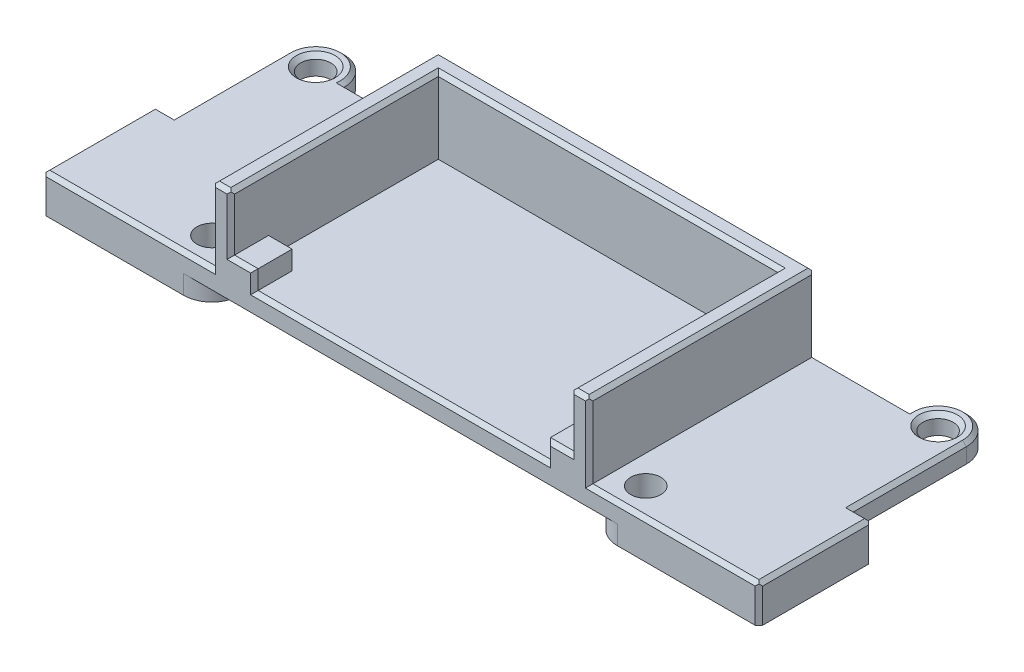
SolidWorks part; units mm, degrees
material "镁合金"
ref_plane "前视基准面" through (0, 0, 0) normal (0, 0, 1) x (1, 0, 0)
ref_plane "上视基准面" through (0, 0, 0) normal (0, 1, 0) x (1, 0, 0)
ref_plane "右视基准面" through (0, 0, 0) normal (1, 0, 0) x (0, 0, -1)
sketch "草图1" plane through (0, 0, 0) normal (0, 1, 0) x (1, 0, 0)
  line L1 (-18, 4) -> (18, 4)
  line L2 (-18, 4) -> (-18, -4)
  line L3 (-18, -4) -> (18, -4)
  line L4 (18, 4) -> (18, -4)
  line L5 (-18, 4) -> (18, -4) construction
  line L6 (-18, -4) -> (18, 4) construction
  line L7 (-18, -4) -> (-15, -4)
  line L8 (-18, -4) -> (-18, -1)
  line L9 (-18, -1) -> (-15, -1)
  line L10 (-15, -4) -> (-15, -1)
  line L11 (18, -4) -> (15, -4)
  line L12 (18, -4) -> (18, -1)
  line L13 (18, -1) -> (15, -1)
  line L14 (15, -4) -> (15, -1)
  line L15 (-19, -2) -> (19, -2)
  line L16 (-19, -2) -> (-19, -8)
  line L17 (-19, -8) -> (19, -8)
  line L18 (19, -2) -> (19, -8)
  circle A0 centre (16.5, 4) radius 1.5
  circle A1 centre (-16.5, 4) radius 1.5
  point P0 (0, 0)
  dimension "D3" = 3
  dimension "D4" = 3
  dimension "D1" = 36
  dimension "D2" = 8
  dimension "D5" = 3
  dimension "D6" = 3
  dimension "D7" = 3
  dimension "D8" = 3
  dimension "D9" = 38
  dimension "D10" = 6
  dimension "D11" = 1
  dimension "D12" = 2
extrude "凸台-拉伸1" add sketch "草图1" along normal blind 1 contours A1 L2 L9 L10 L3 L14 L13 L4 A0 L1 | L1 A1 | L1 A1 | L1 A0 | L1 A0 | L14 L3 L4 L13 | L3 L10 L9 L2 | L15 L10 L3 L14 | L15 L8 L3 L10 | L18 L15 L12 L3 L8 L16 L17 | L15 L14 L3 L12
sketch "草图2" plane through (0, 1, 0) normal (0, 1, 0) x (1, 0, 0)
  line L0 (-9, 3) -> (-9, -7)
  line L1 (-15, 4) -> (15, 4) construction
  line L2 (-10, 4) -> (10, 4)
  line L3 (-10, 4) -> (-10, -8)
  line L4 (-10, -8) -> (10, -8)
  line L5 (10, 4) -> (10, -8)
  line L6 (-19, -8) -> (19, -8) construction
  line L7 (-9, -7) -> (9, -7)
  line L8 (9, 3) -> (9, -7)
  line L9 (-9, 3) -> (9, 3)
  point P9 (0, -8)
  dimension "D1" = 20
  dimension "D2" = 1
extrude "凸台-拉伸4" add sketch "草图2" along normal blind 4
sketch "草图8" plane through (0, 0, 8) normal (0, 0, 1) x (1, 0, 0)
  line L0 (-10, 5) -> (10, 5) construction
  line L1 (-9, 5) -> (9, 5)
  line L2 (-9, 5) -> (-9, 1)
  line L3 (-9, 1) -> (9, 1)
  line L4 (9, 5) -> (9, 1)
  line L5 (-10, 5) -> (-10, 1) construction
  line L6 (10, 5) -> (10, 1) construction
  line L7 (-19, 0) -> (19, 0) construction
  dimension "D1" = 1
  dimension "D2" = 1
  dimension "D3" = 1
extrude "切除-拉伸2" cut sketch "草图8" against normal blind 4
sketch "草图9" plane through (0, 0, 8) normal (0, 0, 1) x (1, 0, 0)
  line L1 (-9, 1) -> (-7.75, 1)
  line L2 (-9, 1) -> (-9, 2)
  line L3 (-9, 2) -> (-7.75, 2)
  line L4 (-7.75, 1) -> (-7.75, 2)
  line L5 (9, 1) -> (7.75, 1)
  line L6 (9, 1) -> (9, 2)
  line L7 (9, 2) -> (7.75, 2)
  line L8 (7.75, 1) -> (7.75, 2)
  dimension "D1" = 1.25
  dimension "D2" = 1
  dimension "D3" = 1
  dimension "D4" = 1.25
extrude "凸台-拉伸5" add sketch "草图9" against normal blind 2
sketch "草图10" plane through (0, 0, 0) normal (0, -1, 0) x (1, 0, 0)
  line L1 (-19, 8) -> (-13, 8)
  line L2 (-19, 8) -> (-19, 2)
  line L3 (-19, 2) -> (-13, 2)
  line L4 (-13, 8) -> (-13, 2)
  line L5 (19, 8) -> (13, 8)
  line L6 (19, 8) -> (19, 2)
  line L7 (19, 2) -> (13, 2)
  line L8 (13, 8) -> (13, 2)
  line L9 (-13, 8) -> (-11.5, 8)
  line L10 (-13, 8) -> (-13, 5)
  line L11 (-13, 5) -> (-11.5, 5)
  line L12 (-11.5, 8) -> (-11.5, 5)
  line L13 (13, 8) -> (11.5, 8)
  line L14 (13, 8) -> (13, 5)
  line L15 (13, 5) -> (11.5, 5)
  line L16 (11.5, 8) -> (11.5, 5)
  circle A0 centre (-11.5, 6.5) radius 1.5
  circle A1 centre (11.5, 6.5) radius 1.5
  line M11 (18, 2) -> (19, 2)
  line M12 (19, 2) -> (19, 8)
  line M13 (19, 8) -> (-19, 8)
  line M14 (-19, 8) -> (-19, 2)
  line M15 (-19, 2) -> (-18, 2)
  dimension "D5" = 3
  dimension "D6" = 1.5
  dimension "D8" = 3
  dimension "D1" = 6
  dimension "D2" = 6
  dimension "D3" = 6
  dimension "D4" = 6
  dimension "D7" = 1.5
extrude "凸台-拉伸6" add sketch "草图10" along normal blind 1 contours L4 L3 L10 M13 M14 M15 | A0 L10 L11 | L12 A0 | L12 A0 | A0 L4 M13 | L16 A1 | L16 A1 | A1 L8 M13 | A1 L15 L14 | L8 L14 L7 M13 M11 M12
hole_wizard "M2 螺纹孔1" positions "草图11" profile "草图12" tap size "M2" standard "GB"
sketch "草图11" plane through (0, 1, 0) normal (0, 1, 0) x (1, 0, 0)
  point P0 (-16.5, 4)
  point P3 (16.5, 4)
sketch "草图12" plane through (-16.5, 1, -4) normal (1, 0, 0) x (0, 0, 1)
  line L0 (0, 0) -> (0, 5.9807)
  line L1 (0, 5.9807) -> (0.8, 5.5)
  line L2 (0.8, 5.5) -> (0.8, 0.225)
  line L3 (0.8, 0.225) -> (1.025, 0)
  line L5 (1.025, 0) -> (0, 0)
  line L6 (-0.8, 0.225) -> (-1.025, 0) construction
  line L10 (0, 5.9807) -> (-0.8, 5.5) construction
  line L11 (0, -6.35) -> (0, 107.95) construction
  dimension "螺纹孔钻头直径" = 1.6
  dimension "螺纹孔钻头深度" = 5.5
  dimension "近端锥形沉头孔直径" = 2.05
  dimension "近端锥形沉头孔角度" = 90
  dimension "导头角度" = 118
cosmetic thread "孔螺蚊线1" parameters "D1"=1, "D2"=2
cosmetic thread "孔螺蚊线2" parameters "D1"=1, "D2"=2
hole_wizard "M2 螺纹孔2" positions "草图13" profile "草图14" tap size "M2" standard "GB" end condition up to next
sketch "草图13" plane through (0, -1, 0) normal (0, -1, 0) x (-1, 0, 0)
  point P0 (11.5, -6.5)
  point P3 (-11.5, -6.5)
cosmetic thread "孔螺蚊线3" parameters "D2"=2
cosmetic thread "孔螺蚊线4" parameters "D2"=2
sketch "草图14" plane through (-11.5, -1, 6.5) normal (1, 0, 0) x (0, 0, -1)
  line L0 (0, 0) -> (0, 2)
  line L1 (0, 2) -> (0.8, 2)
  line L2 (0.8, 2) -> (0.8, 0.225)
  line L3 (0.8, 0.225) -> (1.025, 0)
  line L5 (1.025, 0) -> (0, 0)
  line L6 (-0.8, 0.225) -> (-1.025, 0) construction
  line L11 (0, -6.35) -> (0, 107.95) construction
  dimension "通孔螺纹孔钻头直径" = 1.6
  dimension "通孔螺纹孔钻头深度" = 2
  dimension "近端锥形沉头孔直径" = 2.05
  dimension "近端锥形沉头孔角度" = 90
chamfer "倒角1" distance 0.2 angle 45 8 edges at (9.5, 5, 8) (9, 5, 2.5) (0, 5, -3) (-9, 5, 2.5) (-9.5, 5, 8) (-10, 5, 2) (0, 5, -4) (10, 5, 2)
chamfer "倒角2" distance 0.2 angle 45 12 edges at (-14.5, 1, 8) (-19, 1, 5) (-18.5, 1, 2) (-18, 1, -1) (-16.5, 1, -5.5) (-12.5, 1, -4) (12.5, 1, -4) (16.5, 1, -5.5) (18, 1, -1) (18.5, 1, 2) (19, 1, 5) (14.5, 1, 8)
chamfer "倒角3" distance 0.2 angle 45 11 edges at (7.75, 1.5, 8) (-9, 3.4, 8) (-10, 2.8, 8) (10, 2.8, 8) (-10, 0.9, 7.9) (10, 0.9, 7.9) (0, 1, 8) (-7.75, 1.5, 8) (-8.375, 2, 8) (9, 3.4, 8) (8.375, 2, 8)
chamfer "倒角4" distance 0.2 angle 45 4 edges at (19, -0.1, 2) (19, -0.1, 8) (-19, -0.1, 8) (-19, -0.1, 2)
chamfer "倒角5" distance 0.2 angle 45 2 edges at (-10, 2.8, -4) (10, 2.8, -4)
sketch "草图15" plane through (0, 1, 0) normal (0, 1, 0) x (1, 0, 0)
  line L0 (0, -7.8) -> (0, 3) construction
  line L1 (-7.75, -7.8) -> (7.75, -7.8) construction
  line L2 (9, 3) -> (-9, 3) construction
sketch "草图16" plane through (0, 1, 0) normal (0, 1, 0) x (1, 0, 0)
  circle A0 centre (16.5, 4) radius 0.8 construction
  circle A1 centre (16.5, 4) radius 0.8
  circle A2 centre (11.5, -6.5) radius 0.8 construction
  circle A3 centre (11.5, -6.5) radius 0.8
  circle A4 centre (-11.5, -6.5) radius 0.8 construction
  circle A5 centre (-11.5, -6.5) radius 0.8
  circle A6 centre (-16.5, 4) radius 0.8 construction
  circle A7 centre (-16.5, 4) radius 0.8
extrude "凸台-拉伸7" add sketch "草图16" against normal blind 3
sketch "草图17" plane through (0, 1, 0) normal (0, 1, 0) x (1, 0, 0)
  circle A1 centre (-16.5, 4) radius 0.8
  circle A2 centre (-16.5, 4) radius 0.8
  circle A3 centre (-11.5, -6.5) radius 0.8
  circle A4 centre (-11.5, -6.5) radius 0.8
  circle A5 centre (11.5, -6.5) radius 0.8
  circle A6 centre (11.5, -6.5) radius 0.8
  circle A7 centre (16.5, 4) radius 0.8
  circle A8 centre (16.5, 4) radius 0.8
  dimension "D1" = 0
  dimension "D2" = 0
  dimension "D3" = 0
  dimension "D4" = 0
extrude "切除-拉伸3" cut sketch "草图17" against normal through all
